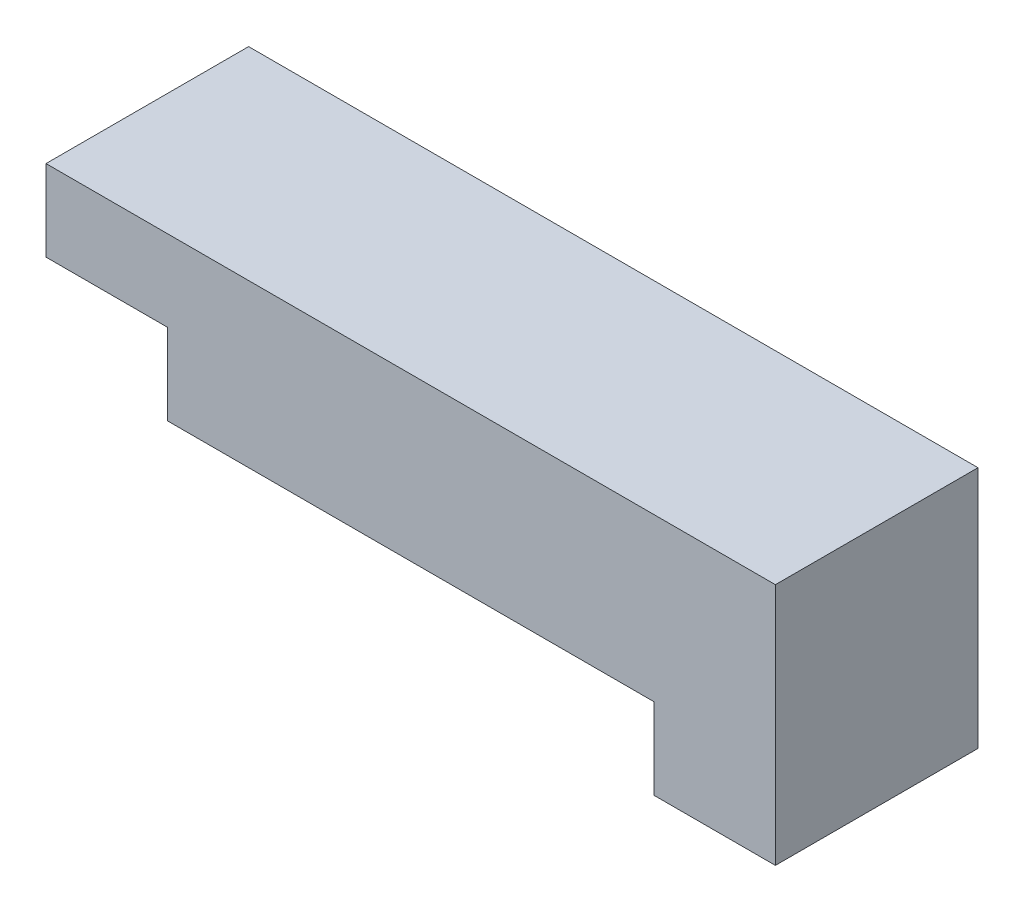
SolidWorks part; units mm, degrees
ref_plane "Front Plane" through (0, 0, 0) normal (0, 0, 1) x (1, 0, 0)
ref_plane "Top Plane" through (0, 0, 0) normal (0, 1, 0) x (1, 0, 0)
ref_plane "Right Plane" through (0, 0, 0) normal (1, 0, 0) x (0, 0, -1)
sketch "Sketch2" plane through (0, 0, 0) normal (0, 1, 0) x (1, 0, 0)
  line L1 (-9, -2.5) -> (9, -2.5)
  line L2 (-9, -2.5) -> (-9, 2.5)
  line L3 (-9, 2.5) -> (9, 2.5)
  line L4 (9, -2.5) -> (9, 2.5)
  line L5 (-9, -2.5) -> (9, 2.5) construction
  line L6 (-9, 2.5) -> (9, -2.5) construction
  point P0 (0, 0)
  dimension "D1" = 5
  dimension "D2" = 18
extrude "Boss-Extrude1" add sketch "Sketch2" along normal blind 6
sketch "Sketch3" plane through (-9, 0, 0) normal (1, 0, 0) x (0, 0, -1)
  line L0 (2.5, 6) -> (2.5, 0) construction
  line L1 (-2.5, 0) -> (1.5, 0)
  line L3 (-0.6, 4) -> (1.5, 4)
  line L4 (1.5, 0) -> (1.5, 4)
  line L5 (-0.6, 4) -> (-0.6, 2)
  line L6 (-0.6, 2) -> (-2.5, 2)
  line L7 (-2.5, 0) -> (2.5, 0) construction
  line L8 (-2.5, 6) -> (-2.5, 0) construction
  line L9 (-2.5, 2) -> (-2.5, 0)
  line L11 (-2.5, 6) -> (2.5, 6) construction
  dimension "D1" = 2
  dimension "D3" = 1
  dimension "D4" = 2
  dimension "D5" = 2.1
extrude "Cut-Extrude1" cut sketch "Sketch3" along normal offset from surface (15 mm away) 3 up to face at (9, 3, 0)
sketch "Sketch4" plane through (0, 0, 2.5) normal (0, 0, 1) x (1, 0, 0)
  line L0 (-9, 6) -> (-9, 2) construction
  line L1 (-9, 4) -> (-6, 4)
  line L2 (-9, 4) -> (-9, 2)
  line L3 (-9, 2) -> (-6, 2)
  line L4 (-6, 4) -> (-6, 2)
  line L5 (-9, 4) -> (-6, 2) construction
  line L6 (-9, 2) -> (-6, 4) construction
  line L7 (6, 2) -> (-9, 2) construction
  point P0 (-7.5, 3)
  dimension "D1" = 2
  dimension "D2" = 3
extrude "Cut-Extrude2" cut sketch "Sketch4" against normal up to next
equation "\"2.75mm-\"=2.75"
